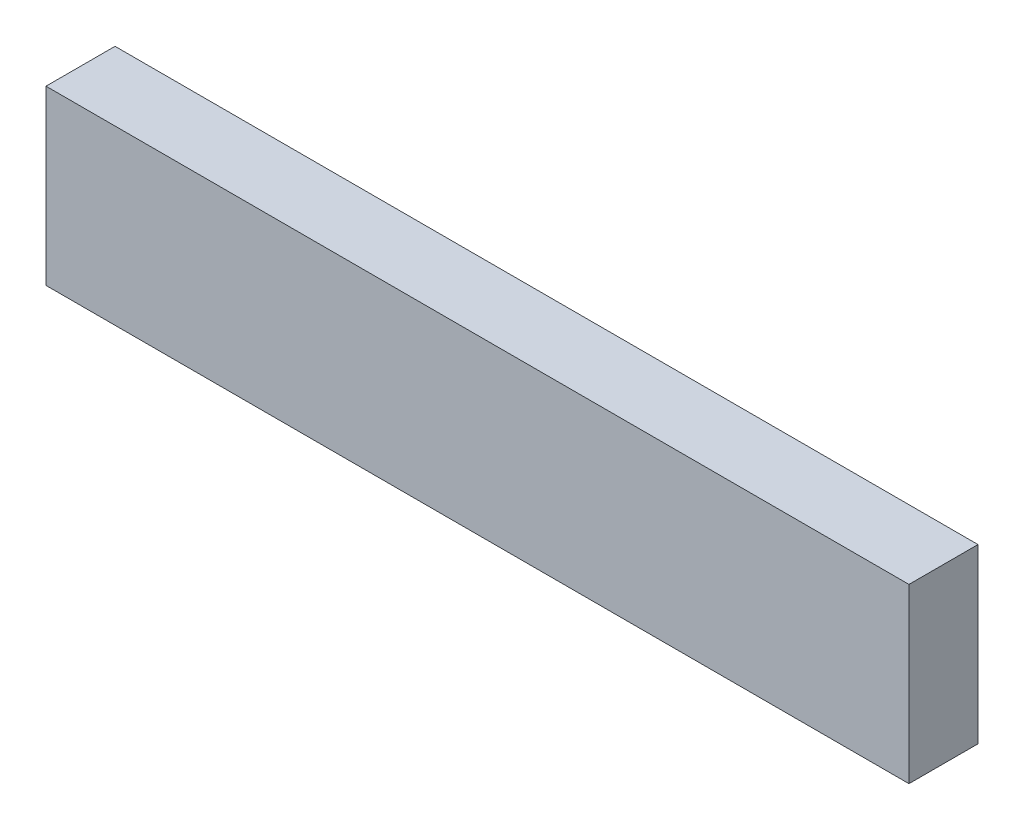
SolidWorks part; units mm, degrees
ref_plane "前视基准面" through (0, 0, 0) normal (0, 0, 1) x (1, 0, 0)
ref_plane "上视基准面" through (0, 0, 0) normal (0, 1, 0) x (1, 0, 0)
ref_plane "右视基准面" through (0, 0, 0) normal (1, 0, 0) x (0, 0, -1)
other "Configuration Table"
sketch "草图1" plane through (0, 0, 0) normal (0, 0, 1) x (1, 0, 0)
  line L1 (-125, -25) -> (125, -25)
  line L2 (-125, -25) -> (-125, 25)
  line L3 (-125, 25) -> (125, 25)
  line L4 (125, -25) -> (125, 25)
  line L5 (-125, -25) -> (125, 25) construction
  line L6 (-125, 25) -> (125, -25) construction
  point P0 (0, 0)
extrude "凸台-拉伸1" add sketch "草图1" along normal blind 20
